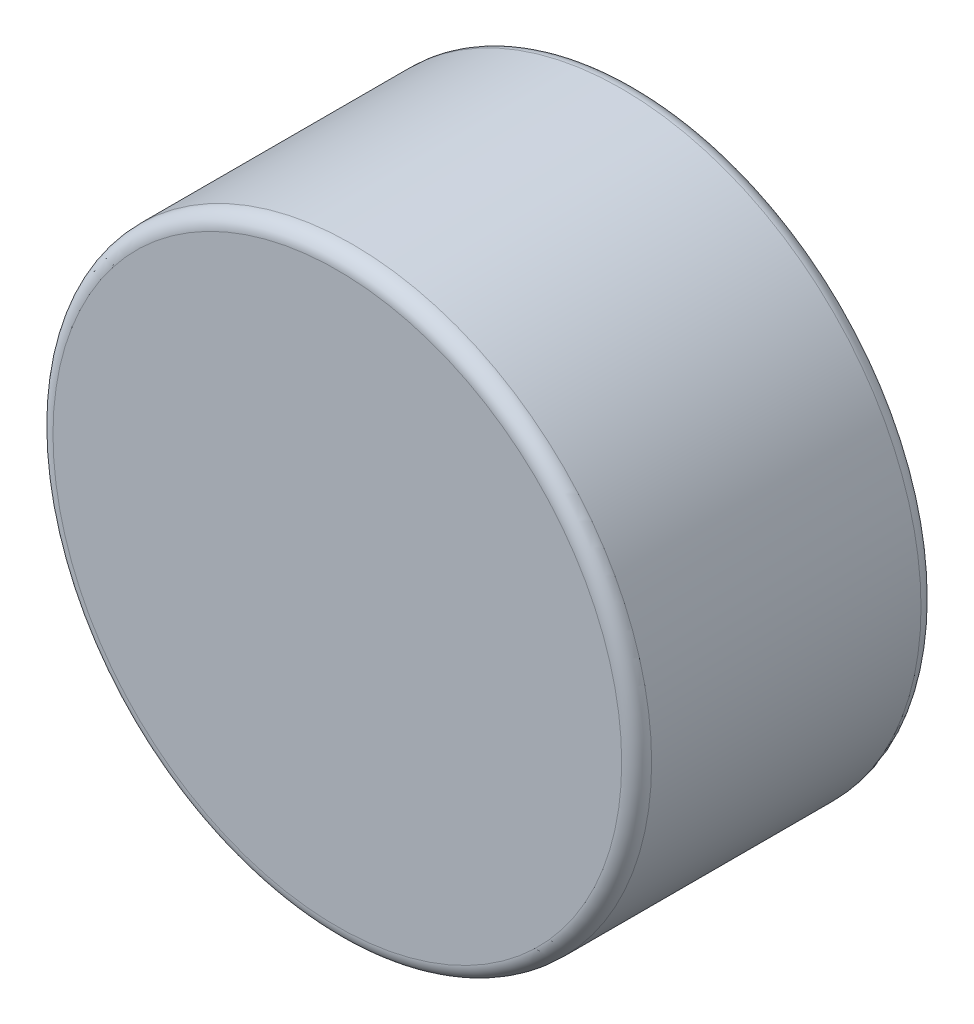
SolidWorks part; units mm, degrees
ref_plane "Front Plane" through (0, 0, 0) normal (0, 0, 1) x (1, 0, 0)
ref_plane "Top Plane" through (0, 0, 0) normal (0, 1, 0) x (1, 0, 0)
ref_plane "Right Plane" through (0, 0, 0) normal (1, 0, 0) x (0, 0, -1)
sketch "Sketch1" plane through (0, 0, 0) normal (1, 0, 0) x (0, 0, -1)
  line L2 (-9.214, 0) -> (9.8521, 0) construction
  line L3 (0, 55) -> (0, -55) construction
  line L4 (0, 0) -> (2, 0)
  line L5 (0, 0) -> (0, 2)
  line L6 (0, 2) -> (2, 2)
  line L7 (2, 0) -> (2, 2)
  dimension "D1" = 4
  dimension "D2" = 2
revolve "Revolve1" add sketch "Sketch1" angle 360 about L2
fillet "Fillet1" radius 0.1 2 edges at (2, 0, -2) (2, 0, 0)
